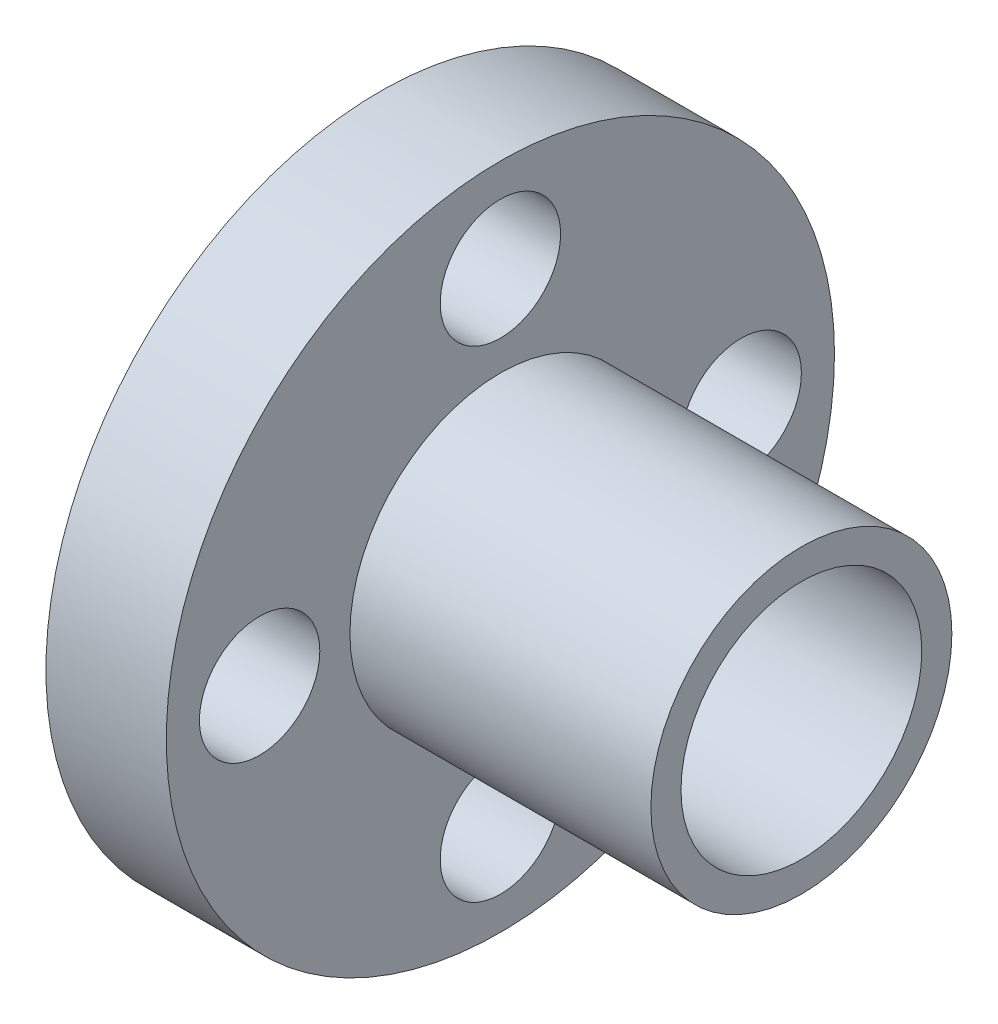
SolidWorks part; units mm, degrees
ref_plane "Front Plane" through (0, 0, 0) normal (0, 0, 1) x (1, 0, 0)
ref_plane "Top Plane" through (0, 0, 0) normal (0, 1, 0) x (1, 0, 0)
ref_plane "Right Plane" through (0, 0, 0) normal (1, 0, 0) x (0, 0, -1)
sketch "Sketch1" plane through (0, 0, 0) normal (1, 0, 0) x (0, 0, -1)
  circle A0 centre (0, 0) radius 11.1
  dimension "D1" = 22.2
extrude "Boss-Extrude1" add sketch "Sketch1" along normal blind 4
sketch "Sketch2" plane through (4, 0, 0) normal (1, 0, 0) x (0, 0, -1)
  circle A0 centre (0, 0) radius 5
  dimension "D1" = 10
extrude "Boss-Extrude2" add sketch "Sketch2" along normal blind 10
sketch "Sketch3" plane through (0, 0, 0) normal (-1, 0, 0) x (0, 0, 1)
  circle A0 centre (0, 0) radius 5
  dimension "D1" = 10
extrude "Boss-Extrude3" add sketch "Sketch3" along normal blind 1.5
sketch "Sketch4" plane through (-1.5, 0, 0) normal (-1, 0, 0) x (0, 0, 1)
  circle A0 centre (0, 0) radius 4
  dimension "D1" = 8
extrude "Cut-Extrude1" cut sketch "Sketch4" against normal through all both and the other way through all
sketch "Sketch5" plane through (4, 0, 0) normal (1, 0, 0) x (0, 0, -1)
  circle A0 centre (0, 8) radius 2
  circle A1 centre (8, 0) radius 2
  circle A2 centre (0, -8) radius 2
  circle A3 centre (-8, 0) radius 2
  point P12 (0, 0)
  dimension "D2" = 4
  dimension "D1" = 8
  dimension "D3" = 4
extrude "Cut-Extrude2" cut sketch "Sketch5" against normal through all both and the other way through all
